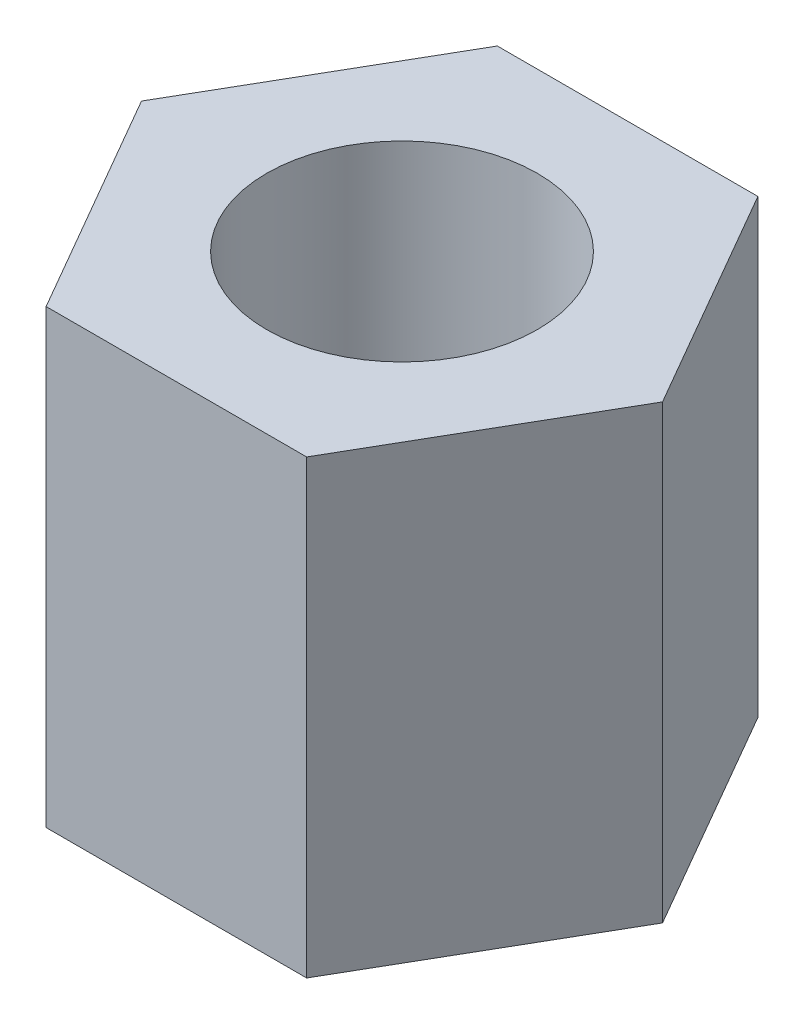
SolidWorks part; units mm, degrees
material "Laiton"
ref_plane "Plan de face" through (0, 0, 0) normal (0, 0, 1) x (1, 0, 0)
ref_plane "Plan de dessus" through (0, 0, 0) normal (0, 1, 0) x (1, 0, 0)
ref_plane "Plan de droite" through (0, 0, 0) normal (1, 0, 0) x (0, 0, -1)
sketch "Esquisse1" plane through (0, 0, 0) normal (0, 1, 0) x (1, 0, 0)
  line L1 (2.8868, 0) -> (1.4434, 2.5)
  line L2 (1.4434, 2.5) -> (-1.4434, 2.5)
  line L3 (-1.4434, 2.5) -> (-2.8868, 0)
  line L4 (-2.8868, 0) -> (-1.4434, -2.5)
  line L5 (-1.4434, -2.5) -> (1.4434, -2.5)
  line L6 (1.4434, -2.5) -> (2.8868, 0)
  circle A0 centre (0, 0) radius 2.5 construction
  circle A1 centre (0, 0) radius 1.5
  dimension "D1" = 5
  dimension "D2" = 3
extrude "Extrusion1" add sketch "Esquisse1" along normal blind 5
